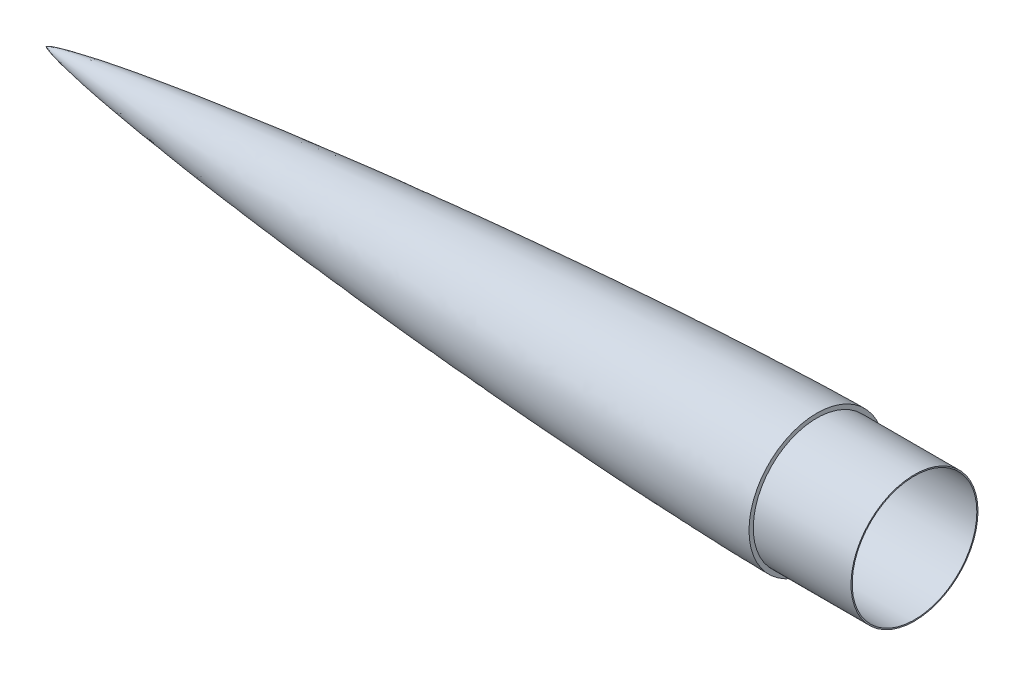
SolidWorks part; units mm, degrees
ref_plane "Front Plane" through (0, 0, 0) normal (0, 0, 1) x (1, 0, 0)
ref_plane "Top Plane" through (0, 0, 0) normal (0, 1, 0) x (1, 0, 0)
ref_plane "Right Plane" through (0, 0, 0) normal (1, 0, 0) x (0, 0, -1)
sketch "Sketch4" plane through (0, 0, 0) normal (0, 0, 1) x (1, 0, 0)
  line L0 (451, 39.65) -> (451, 0)
  line L1 (0.0007, 0) -> (451, 0)
  spline S0 degree 4 poles (0.0007, 0) (0.0025, 0.0043) (0.0068, 0.0123) (0.0184, 0.0266) (0.0449, 0.052) (0.0844, 0.0833) (0.1373, 0.1195) (0.2125, 0.1657) (0.3027, 0.216) (0.4086, 0.2702) (0.5301, 0.3282) (0.7059, 0.4074) (0.9788, 0.5215) (1.4477, 0.7008) (2.2909, 0.9903) (3.8035, 1.4504) (6.5922, 2.1926) (11.8039, 3.3923) (20.9979, 5.2075) (36.3041, 7.802) (57.1012, 10.8381) (82.1427, 14.0646) (109.6945, 17.2509) (137.2762, 20.1641) (164.881, 22.8499) (192.5042, 25.3373) (220.1432, 27.6436) (247.7958, 29.7796) (275.4607, 31.7501) (303.1368, 33.5558) (330.8235, 35.192) (358.5203, 36.6486) (382.7635, 37.7493) (403.5495, 38.5476) (420.3082, 39.0764) (431.5877, 39.3657) (440.852, 39.5472) (446.6507, 39.6227) (449.5502, 39.6468) (451, 39.65) knots 0 0 0 0 0 0.00004 0.000081 0.000162 0.000323 0.000485 0.000646 0.00094 0.001234 0.001534 0.001834 0.002641 0.003843 0.005963 0.009698 0.016588 0.029299 0.05314 0.092371 0.153547 0.214723 0.275899 0.337075 0.398251 0.459427 0.520603 0.581779 0.642954 0.70413 0.765306 0.826482 0.887658 0.918246 0.948834 0.974417 0.987208 1 1 1 1 1 construction
  spline S1 degree 4 poles (0.0007, 0) (0.0025, 0.0043) (0.0068, 0.0123) (0.0184, 0.0266) (0.0449, 0.052) (0.0844, 0.0833) (0.1373, 0.1195) (0.2125, 0.1657) (0.3027, 0.216) (0.4086, 0.2702) (0.5301, 0.3282) (0.7059, 0.4074) (0.9788, 0.5215) (1.4477, 0.7008) (2.2909, 0.9903) (3.8035, 1.4504) (6.5922, 2.1926) (11.8039, 3.3923) (20.9979, 5.2075) (36.3041, 7.802) (57.1012, 10.8381) (82.1427, 14.0646) (109.6945, 17.2509) (137.2762, 20.1641) (164.881, 22.8499) (192.5042, 25.3373) (220.1432, 27.6436) (247.7958, 29.7796) (275.4607, 31.7501) (303.1368, 33.5558) (330.8235, 35.192) (358.5203, 36.6486) (382.7635, 37.7493) (403.5495, 38.5476) (420.3082, 39.0764) (431.5877, 39.3657) (440.852, 39.5472) (446.6507, 39.6227) (449.5502, 39.6468) (451, 39.65) knots 0 0 0 0 0 0.00004 0.000081 0.000162 0.000323 0.000485 0.000646 0.00094 0.001234 0.001534 0.001834 0.002641 0.003843 0.005963 0.009698 0.016588 0.029299 0.05314 0.092371 0.153547 0.214723 0.275899 0.337075 0.398251 0.459427 0.520603 0.581779 0.642954 0.70413 0.765306 0.826482 0.887658 0.918246 0.948834 0.974417 0.987208 1 1 1 1 1
  point P0 (0, 0)
  dimension "D1" = 39.65
revolve "Revolve1" add sketch "Sketch4" angle 360 about L1
ref_plane "Plane1" through (451, 0, 0) normal (1, 0, 0) x (0, 0, -1)
sketch "Sketch7" plane through (451, 0, 0) normal (1, 0, 0) x (0, 0, -1)
  circle A0 centre (0, 0) radius 37.15
  dimension "D1" = 74.3
extrude "Boss-Extrude1" add sketch "Sketch7" along normal blind 57.2
ref_plane "Plane5" through (508.2, 0, 0) normal (1, 0, 0) x (0, 0, -1)
sketch "Sketch10" plane through (508.2, 0, 0) normal (1, 0, 0) x (0, 0, -1)
  circle A0 centre (0, 0) radius 36.465
  dimension "D1" = 72.93
extrude "Cut-Extrude1" cut sketch "Sketch10" along direction (1, 0, 0) on the side against the normal blind 57.2
